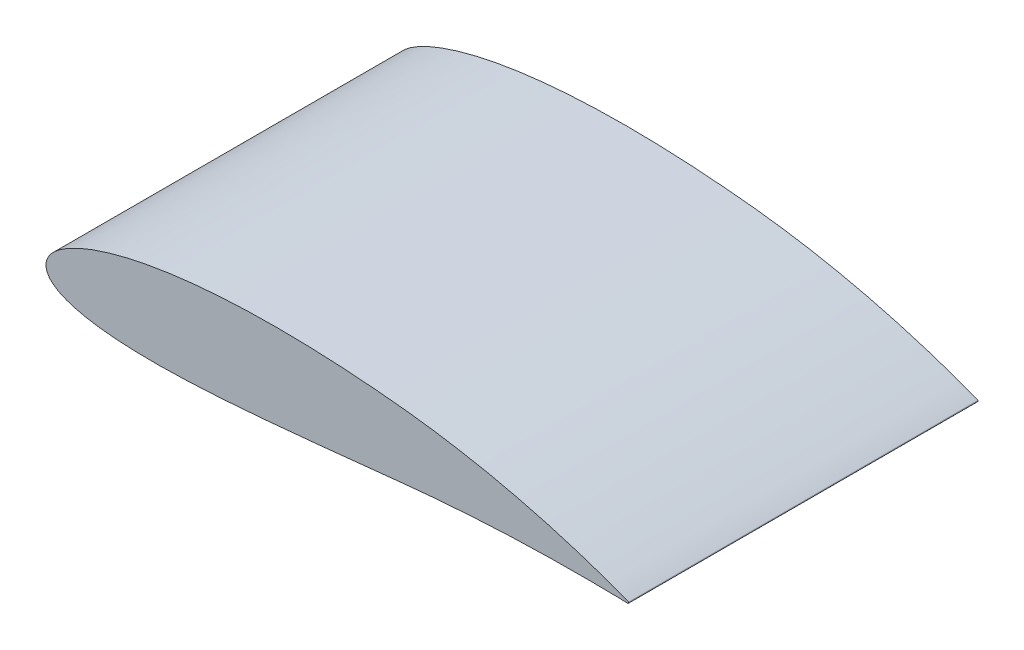
SolidWorks part; units mm, degrees
ref_plane "前视基准面" through (0, 0, 0) normal (0, 0, 1) x (1, 0, 0)
ref_plane "上视基准面" through (0, 0, 0) normal (0, 1, 0) x (1, 0, 0)
ref_plane "右视基准面" through (0, 0, 0) normal (1, 0, 0) x (0, 0, -1)
other "Configuration Table"
curve "Curve8"
  spline degree 3 poles (1.0007, -0.0016, 0) (1.0013, 0.0013, 0) (0.9999, 0.0017, 0) (0.9992, 0.002, 0) (0.998, 0.0024, 0) (0.9963, 0.0031, 0) (0.9942, 0.0039, 0) (0.9916, 0.0049, 0) (0.9885, 0.006, 0) (0.985, 0.0074, 0) (0.9809, 0.0089, 0) (0.9764, 0.0105, 0) (0.9715, 0.0123, 0) (0.9661, 0.0143, 0) (0.9603, 0.0163, 0) (0.954, 0.0185, 0) (0.9472, 0.0209, 0) (0.94, 0.0233, 0) (0.9324, 0.0259, 0) (0.9244, 0.0285, 0) (0.9159, 0.0313, 0) (0.907, 0.0341, 0) (0.8977, 0.0369, 0) (0.888, 0.0399, 0) (0.8779, 0.0429, 0) (0.8675, 0.0459, 0) (0.8566, 0.0489, 0) (0.8454, 0.052, 0) (0.8338, 0.055, 0) (0.8219, 0.0581, 0) (0.8096, 0.0611, 0) (0.797, 0.0641, 0) (0.7841, 0.0671, 0) (0.7709, 0.07, 0) (0.7574, 0.0729, 0) (0.7437, 0.0757, 0) (0.7296, 0.0784, 0) (0.7153, 0.081, 0) (0.7008, 0.0835, 0) (0.686, 0.0859, 0) (0.671, 0.0882, 0) (0.6559, 0.0904, 0) (0.6405, 0.0925, 0) (0.625, 0.0944, 0) (0.6093, 0.0961, 0) (0.5936, 0.0977, 0) (0.5779, 0.0992, 0) (0.5621, 0.1006, 0) (0.5463, 0.1019, 0) (0.5304, 0.1031, 0) (0.5145, 0.1041, 0) (0.4985, 0.1051, 0) (0.4826, 0.1059, 0) (0.4666, 0.1066, 0) (0.4507, 0.1072, 0) (0.4348, 0.1076, 0) (0.419, 0.1079, 0) (0.4032, 0.108, 0) (0.3876, 0.108, 0) (0.372, 0.1079, 0) (0.3566, 0.1076, 0) (0.3413, 0.1072, 0) (0.3262, 0.1066, 0) (0.3113, 0.1059, 0) (0.2965, 0.105, 0) (0.282, 0.104, 0) (0.2677, 0.1028, 0) (0.2536, 0.1014, 0) (0.2397, 0.1, 0) (0.2262, 0.0983, 0) (0.2129, 0.0966, 0) (0.1999, 0.0947, 0) (0.1872, 0.0926, 0) (0.1749, 0.0905, 0) (0.1629, 0.0882, 0) (0.1512, 0.0858, 0) (0.1399, 0.0832, 0) (0.129, 0.0806, 0) (0.1184, 0.0778, 0) (0.1083, 0.075, 0) (0.0985, 0.072, 0) (0.0892, 0.069, 0) (0.0803, 0.0659, 0) (0.0718, 0.0627, 0) (0.0638, 0.0595, 0) (0.0562, 0.0561, 0) (0.0491, 0.0528, 0) (0.0424, 0.0494, 0) (0.0362, 0.0459, 0) (0.0305, 0.0424, 0) (0.0252, 0.0389, 0) (0.0204, 0.0354, 0) (0.0161, 0.0319, 0) (0.0124, 0.0283, 0) (0.0091, 0.0248, 0) (0.0062, 0.0212, 0) (0.0039, 0.0177, 0) (0.0021, 0.0141, 0) (0.0008, 0.0106, 0) (0, 0.007, 0) (-0.0003, 0.0035, 0) (-0.0001, 0, 0) (0.0006, -0.0034, 0) (0.0018, -0.0068, 0) (0.0035, -0.01, 0) (0.0057, -0.0131, 0) (0.0084, -0.016, 0) (0.0115, -0.0189, 0) (0.0151, -0.0216, 0) (0.0192, -0.0242, 0) (0.0237, -0.0267, 0) (0.0287, -0.029, 0) (0.0341, -0.0312, 0) (0.04, -0.0333, 0) (0.0463, -0.0353, 0) (0.053, -0.0372, 0) (0.0602, -0.0389, 0) (0.0677, -0.0405, 0) (0.0757, -0.0419, 0) (0.0841, -0.0433, 0) (0.0929, -0.0445, 0) (0.102, -0.0455, 0) (0.1115, -0.0465, 0) (0.1214, -0.0473, 0) (0.1317, -0.0479, 0) (0.1423, -0.0485, 0) (0.1532, -0.0489, 0) (0.1645, -0.0492, 0) (0.176, -0.0494, 0) (0.1879, -0.0494, 0) (0.2, -0.0493, 0) (0.2125, -0.0491, 0) (0.2252, -0.0488, 0) (0.2382, -0.0484, 0) (0.2514, -0.0479, 0) (0.2648, -0.0472, 0) (0.2785, -0.0465, 0) (0.2924, -0.0457, 0) (0.3065, -0.0448, 0) (0.3207, -0.0438, 0) (0.3352, -0.0427, 0) (0.3497, -0.0416, 0) (0.3645, -0.0403, 0) (0.3794, -0.0391, 0) (0.3944, -0.0377, 0) (0.4094, -0.0363, 0) (0.4246, -0.0349, 0) (0.4399, -0.0334, 0) (0.4552, -0.0319, 0) (0.4706, -0.0304, 0) (0.486, -0.0288, 0) (0.5015, -0.0273, 0) (0.5169, -0.0257, 0) (0.5324, -0.0241, 0) (0.5478, -0.0225, 0) (0.5632, -0.0209, 0) (0.5785, -0.0193, 0) (0.5937, -0.0177, 0) (0.6088, -0.0161, 0) (0.6236, -0.0146, 0) (0.6384, -0.0132, 0) (0.6531, -0.0119, 0) (0.6676, -0.0106, 0) (0.682, -0.0094, 0) (0.6963, -0.0083, 0) (0.7103, -0.0073, 0) (0.7242, -0.0064, 0) (0.7379, -0.0055, 0) (0.7514, -0.0048, 0) (0.7647, -0.0041, 0) (0.7778, -0.0034, 0) (0.7906, -0.0029, 0) (0.8031, -0.0024, 0) (0.8153, -0.0019, 0) (0.8273, -0.0016, 0) (0.8389, -0.0013, 0) (0.8503, -0.001, 0) (0.8613, -0.0008, 0) (0.872, -0.0006, 0) (0.8823, -0.0005, 0) (0.8922, -0.0004, 0) (0.9018, -0.0004, 0) (0.9109, -0.0004, 0) (0.9197, -0.0004, 0) (0.9281, -0.0004, 0) (0.936, -0.0004, 0) (0.9435, -0.0005, 0) (0.9506, -0.0006, 0) (0.9572, -0.0007, 0) (0.9634, -0.0008, 0) (0.9691, -0.0009, 0) (0.9743, -0.001, 0) (0.979, -0.001, 0) (0.9833, -0.0011, 0) (0.9871, -0.0012, 0) (0.9904, -0.0013, 0) (0.9932, -0.0014, 0) (0.9954, -0.0014, 0) (0.9972, -0.0015, 0) (0.9985, -0.0015, 0) (0.9993, -0.0015, 0) (1.0007, -0.0016, 0) (1.0013, 0.0013, 0) (0.9999, 0.0017, 0) knots -0.002016 -0.001646 -0.001523 0 0.000124 0.000494 0.001111 0.001974 0.003082 0.004433 0.006027 0.007862 0.009936 0.012246 0.01479 0.017566 0.02057 0.0238 0.027253 0.030924 0.03481 0.038908 0.043212 0.047719 0.052424 0.057322 0.06241 0.06768 0.073129 0.078752 0.084542 0.090494 0.096602 0.102861 0.109264 0.115806 0.12248 0.129279 0.136198 0.143229 0.150367 0.157604 0.164933 0.172348 0.179841 0.187407 0.195036 0.202674 0.210289 0.217943 0.225627 0.233334 0.241056 0.248787 0.256517 0.26424 0.271947 0.279632 0.287287 0.294904 0.302476 0.309994 0.317454 0.324845 0.332162 0.339398 0.346546 0.353598 0.360549 0.367392 0.374119 0.380726 0.387206 0.393553 0.399762 0.405827 0.411742 0.417504 0.423106 0.428545 0.433817 0.438916 0.44384 0.448585 0.453147 0.457525 0.461715 0.465717 0.469528 0.473149 0.476578 0.479817 0.482867 0.485732 0.488415 0.490923 0.493263 0.495447 0.497489 0.499408 0.501223 0.502964 0.504659 0.506344 0.508028 0.509723 0.511463 0.513277 0.515191 0.517226 0.5194 0.521726 0.524214 0.526872 0.529705 0.532716 0.53591 0.539285 0.542844 0.546585 0.550509 0.554612 0.558894 0.563351 0.56798 0.572781 0.577747 0.582876 0.588164 0.593606 0.5992 0.604939 0.61082 0.616837 0.622986 0.629261 0.635657 0.642168 0.648789 0.655514 0.662336 0.669251 0.676251 0.683332 0.690485 0.697704 0.704983 0.712316 0.719694 0.727113 0.734563 0.742039 0.749534 0.757039 0.764549 0.772056 0.779553 0.787031 0.794485 0.801907 0.809221 0.816444 0.823619 0.830737 0.837794 0.844781 0.851692 0.858521 0.86526 0.871903 0.878444 0.884875 0.89119 0.897383 0.903446 0.909374 0.915161 0.9208 0.926284 0.931608 0.936766 0.941752 0.946561 0.951186 0.955622 0.959865 0.963909 0.96775 0.971382 0.974801 0.978004 0.980986 0.983744 0.986273 0.988572 0.990637 0.992465 0.994054 0.995402 0.996507 0.997368 0.997984 0.998354 0.998477 1 1.000124 1.000494 1.001111 periodic
sketch "Sketch7" plane through (0, 0, 0) normal (0, 0, 1) x (1, 0, 0)
  line L0 (179.5881, 1.5175) -> (29.5881, 1.6223) construction
  line L1 (29.5881, 1.6223) -> (29.6128, 37.0705) construction
  spline S1 degree 3 poles (179.6432, 1.0387) (179.7304, 1.4763) (179.5272, 1.5386) (179.422, 1.5826) (179.2423, 1.6495) (178.9928, 1.7453) (178.6717, 1.8671) (178.2798, 2.0152) (177.8174, 2.1891) (177.2845, 2.3878) (176.6818, 2.611) (176.0095, 2.8575) (175.2681, 3.1264) (174.4583, 3.4172) (173.5805, 3.7283) (172.6354, 4.0589) (171.6237, 4.4076) (170.5461, 4.7735) (169.4034, 5.1547) (168.1965, 5.5504) (166.9264, 5.9589) (165.5939, 6.3786) (164.2003, 6.8086) (162.7465, 7.2468) (161.2337, 7.6919) (159.6633, 8.1424) (158.0363, 8.5964) (156.3543, 9.0528) (154.6186, 9.5096) (152.8309, 9.9656) (150.9924, 10.4187) (149.105, 10.8676) (147.1702, 11.3108) (145.1898, 11.7466) (143.1656, 12.1735) (141.0994, 12.59) (138.9932, 12.9947) (136.8491, 13.3859) (134.6688, 13.7623) (132.4547, 14.1227) (130.2087, 14.4654) (127.9331, 14.7894) (125.6302, 15.0933) (123.3022, 15.3759) (120.9566, 15.6356) (118.6031, 15.8706) (116.246, 16.0936) (113.8827, 16.3) (111.5084, 16.4908) (109.1258, 16.6655) (106.7372, 16.8224) (104.3451, 16.962) (101.9519, 17.0828) (99.5602, 17.1846) (97.1724, 17.2668) (94.7911, 17.329) (92.4186, 17.3703) (90.0576, 17.3907) (87.7106, 17.3896) (85.38, 17.3667) (83.0683, 17.3218) (80.778, 17.2545) (78.5115, 17.1651) (76.2713, 17.0529) (74.0598, 16.9184) (71.8793, 16.7614) (69.7322, 16.5819) (67.6207, 16.3804) (65.5472, 16.1569) (63.5139, 15.9115) (61.523, 15.6453) (59.5764, 15.3582) (57.6765, 15.0508) (55.825, 14.7238) (54.0241, 14.3778) (52.2756, 14.0136) (50.5812, 13.632) (48.9428, 13.2336) (47.362, 12.8195) (45.8404, 12.3903) (44.3796, 11.9476) (42.981, 11.4918) (41.646, 11.0239) (40.3758, 10.5453) (39.1718, 10.0569) (38.035, 9.5595) (36.9664, 9.0546) (35.9671, 8.5427) (35.0378, 8.0252) (34.1795, 7.5028) (33.3929, 6.9766) (32.6785, 6.4474) (32.0366, 5.9164) (31.4685, 5.3835) (30.9736, 4.8501) (30.5531, 4.3163) (30.2069, 3.7827) (29.9354, 3.2495) (29.7396, 2.7171) (29.6192, 2.1861) (29.5756, 1.6569) (29.6082, 1.1327) (29.7151, 0.6185) (29.8965, 0.1195) (30.1516, -0.3612) (30.4792, -0.8234) (30.8783, -1.2672) (31.3484, -1.6924) (31.8886, -2.0993) (32.4983, -2.4876) (33.1766, -2.8578) (33.923, -3.2095) (34.7366, -3.5424) (35.6166, -3.8566) (36.562, -4.1519) (37.572, -4.4279) (38.6453, -4.6848) (39.7809, -4.9221) (40.9777, -5.14) (42.2344, -5.3382) (43.5498, -5.5166) (44.9225, -5.6754) (46.3511, -5.8144) (47.8344, -5.9335) (49.3708, -6.0332) (50.9588, -6.1131) (52.5969, -6.174) (54.2837, -6.2157) (56.0175, -6.2387) (57.7966, -6.243) (59.6196, -6.2293) (61.4846, -6.1981) (63.3901, -6.1496) (65.3341, -6.0844) (67.3151, -6.0035) (69.3312, -5.9067) (71.3806, -5.7954) (73.4614, -5.6699) (75.5718, -5.5309) (77.7099, -5.3798) (79.8738, -5.2162) (82.0615, -5.0423) (84.2711, -4.8576) (86.5006, -4.6642) (88.7479, -4.4617) (91.0111, -4.252) (93.2881, -4.0351) (95.5768, -3.8126) (97.875, -3.5847) (100.1808, -3.3526) (102.4919, -3.1167) (104.8063, -2.8783) (107.1216, -2.6377) (109.436, -2.3958) (111.7469, -2.1533) (114.0525, -1.9108) (116.3503, -1.6688) (118.6313, -1.4294) (120.8883, -1.1897) (123.1209, -0.9627) (125.3344, -0.7478) (127.5317, -0.5453) (129.7107, -0.3545) (131.8692, -0.1763) (134.0051, -0.0103) (136.1162, 0.1437) (138.2003, 0.2856) (140.2554, 0.4159) (142.2793, 0.5345) (144.2699, 0.6419) (146.225, 0.7383) (148.1426, 0.8243) (150.0206, 0.9002) (151.8569, 0.9665) (153.6496, 1.0238) (155.3967, 1.0725) (157.0961, 1.113) (158.7461, 1.1462) (160.3446, 1.1723) (161.89, 1.1924) (163.3803, 1.2064) (164.8139, 1.2153) (166.189, 1.2197) (167.5041, 1.22) (168.7575, 1.2167) (169.9479, 1.2106) (171.0736, 1.202) (172.1335, 1.1914) (173.1261, 1.1794) (174.0503, 1.1663) (174.9049, 1.1529) (175.6888, 1.1389) (176.4011, 1.1255) (177.0409, 1.1123) (177.6074, 1.1) (178.0997, 1.0888) (178.5174, 1.0789) (178.8599, 1.0702) (179.1266, 1.0645) (179.3179, 1.0577) (179.4317, 1.0579) (179.6432, 1.0387) (179.7304, 1.4763) (179.5272, 1.5386) knots -0.002016 -0.001646 -0.001523 0 0.000124 0.000494 0.001111 0.001974 0.003082 0.004433 0.006027 0.007862 0.009936 0.012246 0.01479 0.017566 0.02057 0.0238 0.027253 0.030924 0.03481 0.038908 0.043212 0.047719 0.052424 0.057322 0.06241 0.06768 0.073129 0.078752 0.084542 0.090494 0.096602 0.102861 0.109264 0.115806 0.12248 0.129279 0.136198 0.143229 0.150367 0.157604 0.164933 0.172348 0.179841 0.187407 0.195036 0.202674 0.210289 0.217943 0.225627 0.233334 0.241056 0.248787 0.256517 0.26424 0.271947 0.279632 0.287287 0.294904 0.302476 0.309994 0.317454 0.324845 0.332162 0.339398 0.346546 0.353598 0.360549 0.367392 0.374119 0.380726 0.387206 0.393553 0.399762 0.405827 0.411742 0.417504 0.423106 0.428545 0.433817 0.438916 0.44384 0.448585 0.453147 0.457525 0.461715 0.465717 0.469528 0.473149 0.476578 0.479817 0.482867 0.485732 0.488415 0.490923 0.493263 0.495447 0.497489 0.499408 0.501223 0.502964 0.504659 0.506344 0.508028 0.509723 0.511463 0.513277 0.515191 0.517226 0.5194 0.521726 0.524214 0.526872 0.529705 0.532716 0.53591 0.539285 0.542844 0.546585 0.550509 0.554612 0.558894 0.563351 0.56798 0.572781 0.577747 0.582876 0.588164 0.593606 0.5992 0.604939 0.61082 0.616837 0.622986 0.629261 0.635657 0.642168 0.648789 0.655514 0.662336 0.669251 0.676251 0.683332 0.690485 0.697704 0.704983 0.712316 0.719694 0.727113 0.734563 0.742039 0.749534 0.757039 0.764549 0.772056 0.779553 0.787031 0.794485 0.801907 0.809221 0.816444 0.823619 0.830737 0.837794 0.844781 0.851692 0.858521 0.86526 0.871903 0.878444 0.884875 0.89119 0.897383 0.903446 0.909374 0.915161 0.9208 0.926284 0.931608 0.936766 0.941752 0.946561 0.951186 0.955622 0.959865 0.963909 0.96775 0.971382 0.974801 0.978004 0.980986 0.983744 0.986273 0.988572 0.990637 0.992465 0.994054 0.995402 0.996507 0.997368 0.997984 0.998354 0.998477 1 1.000124 1.000494 1.001111 only from (179.5881, 1.5175) to (179.5881, 1.5175)
  dimension "D1" = 150
extrude "Boss-Extrude3" add sketch "Sketch7" along normal blind 90
